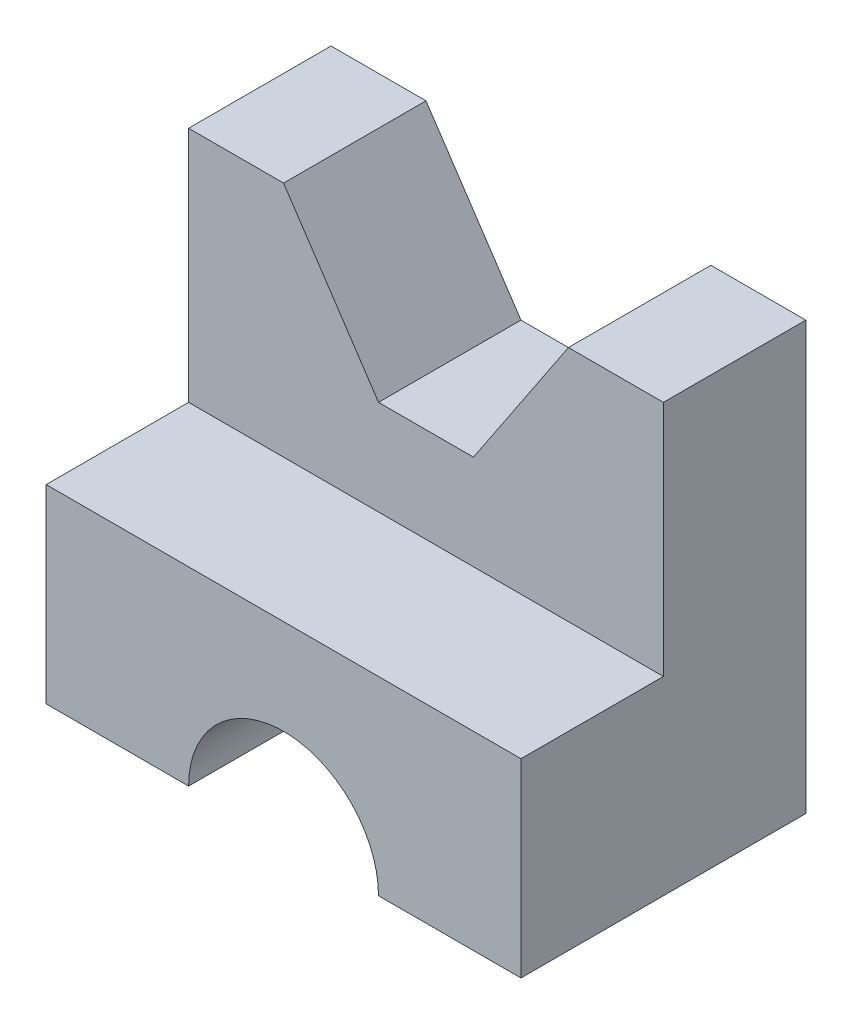
SolidWorks part; units mm, degrees
ref_plane "Alzado" through (0, 0, 0) normal (0, 0, 1) x (1, 0, 0)
ref_plane "Planta" through (0, 0, 0) normal (0, 1, 0) x (1, 0, 0)
ref_plane "Vista lateral" through (0, 0, 0) normal (1, 0, 0) x (0, 0, -1)
sketch "Croquis2" plane through (0, 0, 0) normal (1, 0, 0) x (0, 0, -1)
  line L0 (0, 0) -> (0, 45)
  line L1 (0, 45) -> (-15, 45)
  line L2 (-15, 45) -> (-15, 20)
  line L3 (-15, 20) -> (-30, 20)
  line L4 (-30, 20) -> (-30, 0)
  line L5 (-30, 0) -> (0, 0)
  dimension "D1" = 45
  dimension "D2" = 20
  dimension "D3" = 15
  dimension "D4" = 30
extrude "Saliente-Extruir1" add sketch "Croquis2" along normal mid plane 50
sketch "Croquis4" plane through (0, 0, 0) normal (0, 0, 1) x (1, 0, 0)
  line L0 (-10, 0) -> (10, 0)
  line L1 (-15, 45) -> (-5, 30)
  line L2 (25, 45) -> (-25, 45) construction
  line L3 (-5, 30) -> (5, 30)
  line L4 (5, 30) -> (15, 45)
  line L5 (15, 45) -> (-15, 45)
  arc A0 (10, 0) -> (-10, 0) centre (0, 0) ccw
  point P8 (0, 45)
  dimension "D1" = 10
  dimension "D2" = 10
  dimension "D3" = 30
  dimension "D4" = 15
extrude "Cortar-Extruir2" cut sketch "Croquis4" along normal up to next
